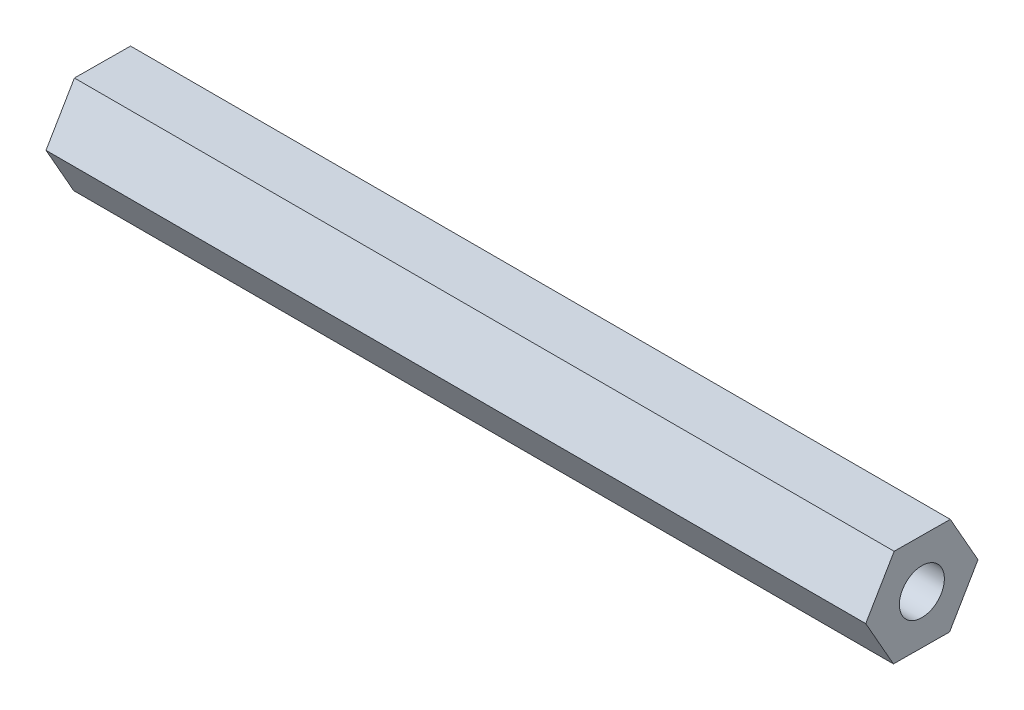
SolidWorks part; units mm, degrees
ref_plane "Front Plane" through (0, 0, 0) normal (0, 0, 1) x (1, 0, 0)
ref_plane "Top Plane" through (0, 0, 0) normal (0, 1, 0) x (1, 0, 0)
ref_plane "Right Plane" through (0, 0, 0) normal (1, 0, 0) x (0, 0, -1)
sketch "Sketch1" plane through (0, 0, 0) normal (1, 0, 0) x (0, 0, -1)
  line L1 (1.9946, -3.5133) -> (4.0399, -0.0292)
  line L2 (4.0399, -0.0292) -> (2.0453, 3.484)
  line L3 (2.0453, 3.484) -> (-1.9946, 3.5133)
  line L4 (-1.9946, 3.5133) -> (-4.0399, 0.0292)
  line L5 (-4.0399, 0.0292) -> (-2.0453, -3.484)
  line L6 (-2.0453, -3.484) -> (1.9946, -3.5133)
  circle A0 centre (0, 0) radius 3.4987 construction
  circle A1 centre (0, 0) radius 1.62
  dimension "D2" = 3.24
  dimension "D1" = 4.04
extrude "Boss-Extrude1" add sketch "Sketch1" along normal blind 59
